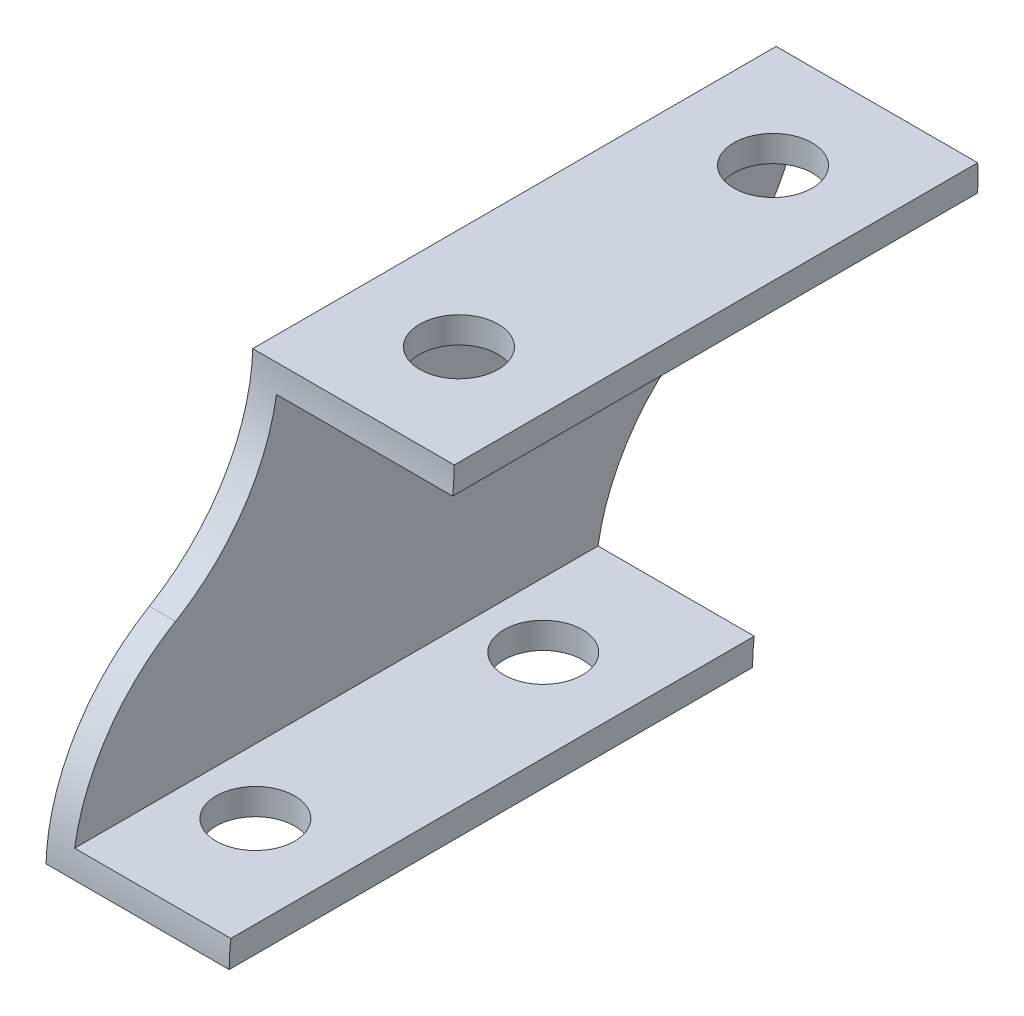
SolidWorks part; units mm, degrees
ref_plane "Front Plane" through (0, 0, 0) normal (0, 0, 1) x (1, 0, 0)
ref_plane "Top Plane" through (0, 0, 0) normal (0, 1, 0) x (1, 0, 0)
ref_plane "Right Plane" through (0, 0, 0) normal (1, 0, 0) x (0, 0, -1)
sketch "Sketch1" plane through (0, 0, 0) normal (0, 0, 1) x (1, 0, 0)
  line L0 (397.8242, 16) -> (397.4239, 2.5)
  line L1 (397.8242, 16) -> (405.5242, 16)
  line L2 (405.5242, 16) -> (405.5242, 15)
  line L3 (405.5242, 15) -> (398.795, 15)
  line L4 (398.795, 15) -> (398.454, 3.5)
  line L5 (397.4239, 2.5) -> (405.4239, 2.5)
  line L7 (405.4239, 2.5) -> (405.4239, 3.5)
  line L9 (405.4239, 3.5) -> (398.454, 3.5)
  dimension "D2" = 1
  dimension "D3" = 1
  dimension "D4" = 1
extrude "Boss-Extrude1" add sketch "Sketch1" along normal blind 28.5
sketch "Sketch5" plane through (0, 16, 0) normal (0, 1, 0) x (1, 0, 0)
  line L0 (405.5242, 0) -> (397.8242, 0) construction
  circle A0 centre (401.7035, -5) radius 1.5
  circle A1 centre (401.7035, -17) radius 1.5
  dimension "D1" = 5
  dimension "D2" = 12
sketch "Sketch11" plane through (405.5242, 0, 0) normal (1, 0, 0) x (0, 0, -1)
  line L0 (-28.5, 2.5) -> (0, 2.5) construction
  line L1 (0, 16) -> (-1, 16)
  line L2 (0, 16) -> (0, 2.5)
  line L3 (0, 2.5) -> (-1, 2.5)
  line L4 (-1, 16) -> (-1, 2.5)
  line L5 (-28.5, 16) -> (-21, 16)
  line L6 (-28.5, 16) -> (0, 16) construction
  line L7 (-28.5, 16) -> (-28.5, 2.5)
  line L8 (-1, 2.5) -> (-2.5, 2.5)
  line L9 (-21, 16) -> (-1, 16)
  line L10 (-28.5, 2.5) -> (-8.5, 2.5)
  line L11 (-8.5, 2.5) -> (-8.5, 16)
  line L12 (-8.5, 2.5) -> (0, 2.5)
  arc A0 (-28.5, 2.5) -> (-24.75, 9.25) centre (-20.55, 2.5) cw
  arc A1 (-24.75, 9.25) -> (-21, 16) centre (-28.95, 16) ccw
  arc A2 (-8.5, 2.5) -> (-4.6146, 9.25) centre (-0.694, 2.5) cw
  arc A3 (-4.6146, 9.25) -> (-1, 16) centre (-8.2757, 15.5533) ccw
  line M5 (0, 15) -> (0, 16)
  line M6 (0, 16) -> (-28.5, 16)
  line M7 (-28.5, 16) -> (-28.5, 15)
  line M8 (-28.5, 15) -> (0, 15)
  dimension "D1" = 1
  dimension "D2" = 20
  dimension "D3" = 20
extrude "Cut-Extrude4" cut sketch "Sketch5" against normal blind 1
extrude "Cut-Extrude5" cut sketch "Sketch11" against normal blind 10 contours A0 A1 L7 M8 | A1 M8 M6 M7 | L4 L3 L2 M8 | A3 L4 M8 M5 M6 | A3 A2 L12 L8 L4 M8
sketch "Sketch12" plane through (405.4239, 0, 0) normal (1, 0, 0) x (0, 0, -1)
  line L1 (-28.8266, 3.5129) -> (-7.9831, 3.5129)
  line L2 (-28.8266, 3.5129) -> (-28.8266, 2.1786)
  line L3 (-28.8266, 2.1786) -> (-7.9831, 2.1786)
  line L4 (-7.9831, 3.5129) -> (-7.9831, 2.1786)
extrude "Cut-Extrude7" cut sketch "Sketch12" against normal blind 1
sketch "Sketch13" plane through (0, 2.5, 0) normal (0, -1, 0) x (1, 0, 0)
  line L2 (397.4239, 28.5) -> (397.4239, 8.5) construction
  line L4 (397.4239, 8.5) -> (404.4239, 8.5) construction
  circle A0 centre (400.9239, 24) radius 1.5
  circle A1 centre (400.9239, 13) radius 1.5
  dimension "D1" = 3.5
  dimension "D3" = 11
  dimension "D2" = 4.5
extrude "Cut-Extrude8" cut sketch "Sketch13" against normal blind 1
